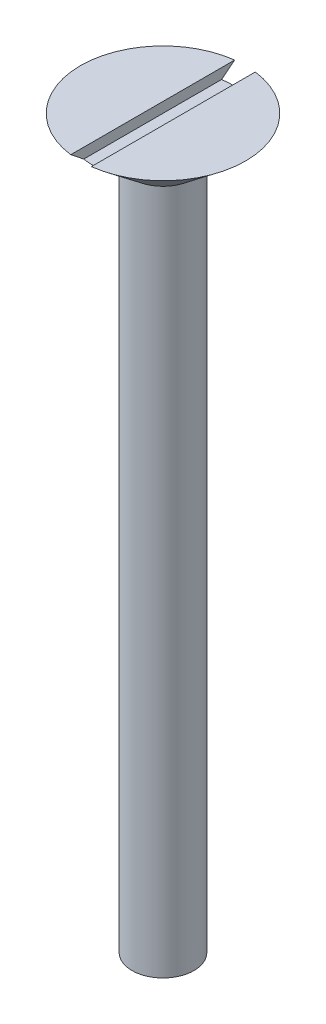
SolidWorks part; units mm, degrees
material "Alloy Steel"
ref_plane "Front Plane" through (0, 0, 0) normal (0, 0, 1) x (1, 0, 0)
ref_plane "Top Plane" through (0, 0, 0) normal (0, 1, 0) x (1, 0, 0)
ref_plane "Right Plane" through (0, 0, 0) normal (1, 0, 0) x (0, 0, -1)
sketch "Sketch6" plane through (0, 0, 0) normal (0, 0, 1) x (1, 0, 0)
  line L0 (0, 0) -> (4, 0)
  line L1 (4, 0) -> (1.5, -2)
  line L2 (1.5, -2) -> (0, -2)
  line L3 (0, -2) -> (0, 0)
  line L4 (0, 0) -> (0, 4.7813) construction
  dimension "D1" = 4
  dimension "D2" = 1.5
  dimension "D3" = 2
revolve "Revolve1" add sketch "Sketch6" angle 360 about L4
sketch "Sketch7" plane through (0, 0, 0) normal (0, 1, 0) x (1, 0, 0)
  line L1 (-0.5, -4.1541) -> (0.5, -4.1541)
  line L2 (-0.5, -4.1541) -> (-0.5, 4.1541)
  line L3 (-0.5, 4.1541) -> (0.5, 4.1541)
  line L4 (0.5, -4.1541) -> (0.5, 4.1541)
  line L5 (-0.5, -4.1541) -> (0.5, 4.1541) construction
  line L6 (-0.5, 4.1541) -> (0.5, -4.1541) construction
  point P0 (0, 0)
  dimension "D1" = 1
extrude "Cut-Extrude3" cut sketch "Sketch7" against normal blind 0.5
sketch "Sketch8" plane through (0, -2, 0) normal (0, -1, 0) x (1, 0, 0)
  circle A0 centre (0, 0) radius 1.5
extrude "Boss-Extrude3" add sketch "Sketch8" along normal blind 33.2
